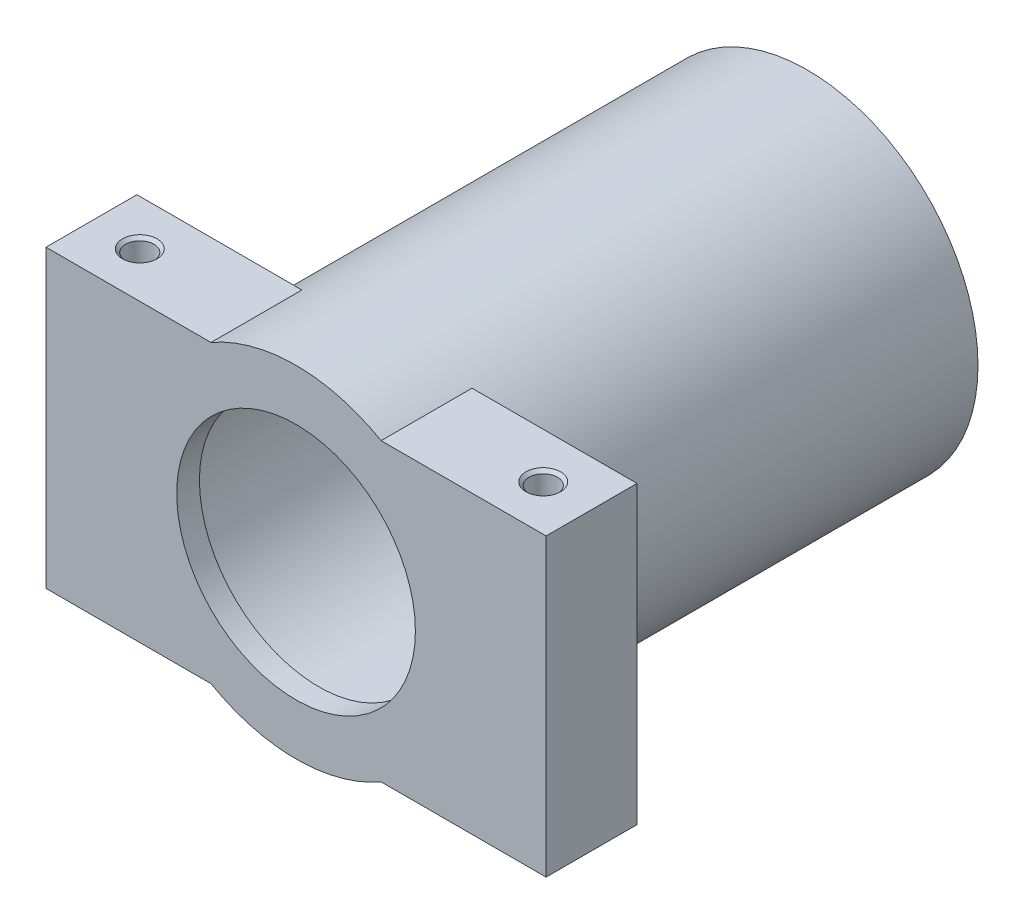
SolidWorks part; units mm, degrees
material "6061 合金"
ref_plane "前视基准面" through (0, 0, 0) normal (0, 0, 1) x (1, 0, 0)
ref_plane "上视基准面" through (0, 0, 0) normal (0, 1, 0) x (1, 0, 0)
ref_plane "右视基准面" through (0, 0, 0) normal (1, 0, 0) x (0, 0, -1)
sketch "草图1" plane through (0, 0, 0) normal (0, 0, 1) x (1, 0, 0)
  circle A0 centre (0, 0) radius 15
  circle A1 centre (0, 0) radius 12.5
  dimension "D1" = 30
  dimension "D2" = 25
extrude "凸台-拉伸1" add sketch "草图1" along normal blind 45
sketch "草图2" plane through (0, 0, 45) normal (0, 0, 1) x (1, 0, 0)
  line L1 (22, -13) -> (-22, -13)
  line L2 (22, -13) -> (22, 13)
  line L3 (22, 13) -> (-22, 13)
  line L4 (-22, -13) -> (-22, 13)
  line L5 (22, -13) -> (-22, 13) construction
  line L6 (22, 13) -> (-22, -13) construction
  circle A0 centre (0, 0) radius 10.5
  point P0 (0, 0)
  dimension "D3" = 21
  dimension "D1" = 26
  dimension "D2" = 44
extrude "凸台-拉伸2" add sketch "草图2" against normal blind 8
sketch "草图4" plane through (0, 13, 0) normal (0, 1, 0) x (1, 0, 0)
  line L0 (0, -45) -> (0, 0) construction
  line L1 (-7.4833, -45) -> (7.4833, -45) construction
  line L2 (-22, -41) -> (22, -41) construction
  line L3 (-22, -37) -> (-22, -45) construction
  line L4 (22, -37) -> (22, -45) construction
  point P11 (0, -23)
  point P12 (-17.75, -41)
  point P13 (17.75, -41)
  dimension "D1" = 22
  dimension "D2" = 17.75
  dimension "D3" = 17.75
hole_wizard "M3 螺纹孔1" positions "3D草图1" profile "草图5" tap size "M3" standard "GB"
sketch3d "3D草图1"
  point P0 (-17.75, 13, 41)
  point P3 (17.75, 13, 41)
  point P6 (0, 13, 23)
sketch "草图5" plane through (-17.75, 13, 41) normal (1, 0, 0) x (0, 0, 1)
  line L0 (0, 0) -> (0, 28)
  line L1 (0, 28) -> (1.25, 28)
  line L2 (1.25, 28) -> (1.25, 0.275)
  line L3 (1.25, 0.275) -> (1.525, 0)
  line L5 (1.525, 0) -> (0, 0)
  line L6 (-1.25, 0.275) -> (-1.525, 0) construction
  line L11 (0, -6.35) -> (0, 107.95) construction
  dimension "通孔螺纹孔钻头直径" = 2.5
  dimension "通孔螺纹孔钻头深度" = 28
  dimension "近端锥形沉头孔直径" = 3.05
  dimension "近端锥形沉头孔角度" = 90
cosmetic thread "孔螺蚊线1" parameters "D2"=3
cosmetic thread "孔螺蚊线2" parameters "D2"=3
cosmetic thread "孔螺蚊线3" parameters "D2"=3
sketch "草图6" plane through (0, 0, 0) normal (0, 0, -1) x (-1, 0, 0)
  circle A0 centre (0, 0) radius 12.5
extrude "切除-拉伸1" cut sketch "草图6" against normal blind 43
